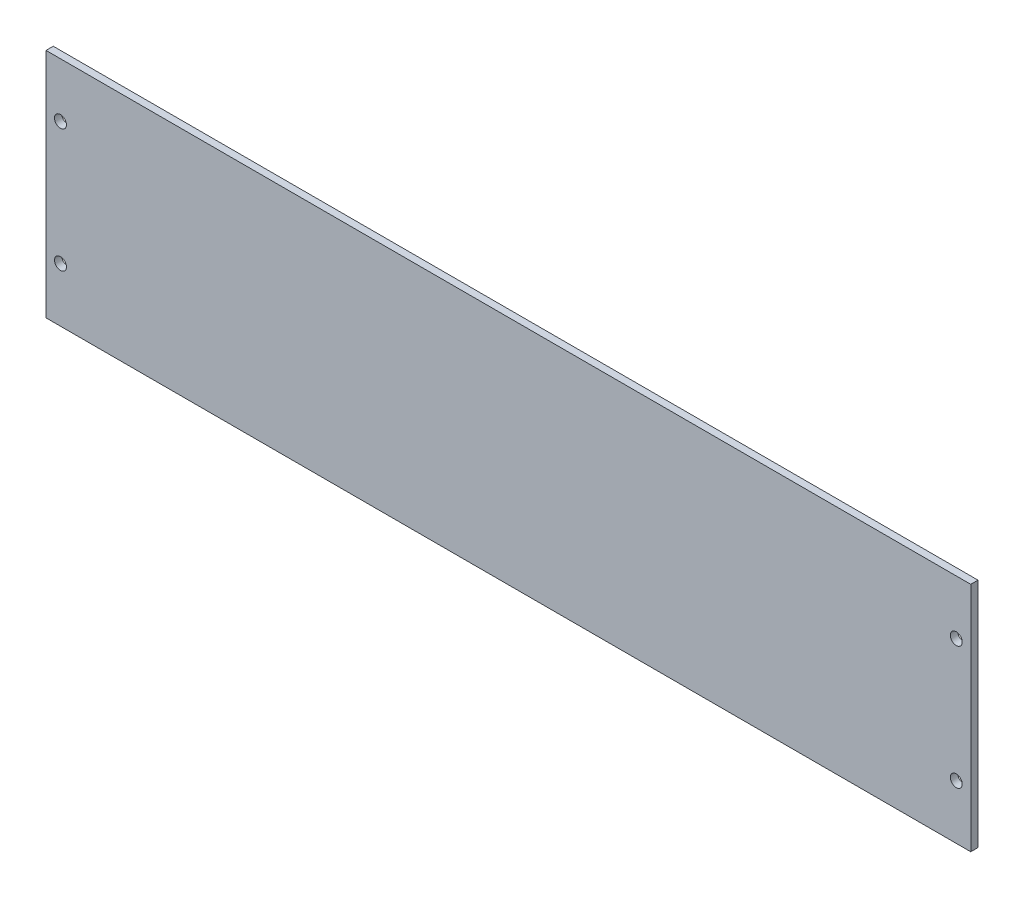
SolidWorks part; units mm, degrees
ref_plane "Plan de face" through (0, 0, 0) normal (0, 0, 1) x (1, 0, 0)
ref_plane "Plan de dessus" through (0, 0, 0) normal (0, 1, 0) x (1, 0, 0)
ref_plane "Plan de droite" through (0, 0, 0) normal (1, 0, 0) x (0, 0, -1)
sketch "Esquisse1" plane through (0, 0, 0) normal (0, 0, 1) x (1, 0, 0)
  line L1 (-255.5, -64) -> (255.5, -64)
  line L2 (-255.5, -64) -> (-255.5, 64)
  line L3 (-255.5, 64) -> (255.5, 64)
  line L4 (255.5, -64) -> (255.5, 64)
  line L5 (-255.5, -64) -> (255.5, 64) construction
  line L6 (-255.5, 64) -> (255.5, -64) construction
  point P0 (0, 0)
  dimension "D1" = 128
  dimension "D2" = 511
extrude "Boss.-Extru.1" add sketch "Esquisse1" along normal blind 4
sketch "Esquisse2" plane through (0, 0, 0) normal (0, 0, -1) x (-1, 0, 0)
  line L0 (255.5, -64) -> (-255.5, -64) construction
  line L1 (247.5, -56) -> (-247.5, -56) construction
  line L2 (247.5, -56) -> (247.5, 56) construction
  line L3 (247.5, 56) -> (-247.5, 56) construction
  line L4 (-247.5, -56) -> (-247.5, 56) construction
  line L5 (247.5, -56) -> (-247.5, 56) construction
  line L6 (247.5, 56) -> (-247.5, -56) construction
  line L7 (-255.5, -64) -> (-255.5, 64) construction
  line L8 (-153.9304, 0) -> (204.6118, 0) construction
  line L9 (0, -141.2759) -> (0, 199.6584) construction
  point P0 (0, 0)
  point P14 (-247.5, -34)
  point P15 (-247.5, 34)
  point P16 (247.5, -34)
  point P17 (247.5, 34)
  point P18 (0, 56)
  dimension "D1" = 8
  dimension "D2" = 8
  dimension "D3" = 30
hole_wizard "Dégagement M61" positions "Esquisse3D1" profile "Esquisse3" hole size "M6" standard "ISO" end condition through all
sketch3d "Esquisse3D1"
  point P3 (-247.5, 34, 0)
  point P6 (-247.5, -34, 0)
  point P9 (247.5, -34, 0)
  point P12 (247.5, 34, 0)
sketch "Esquisse3" plane through (-247.5, 34, 0) normal (1, 0, 0) x (0, 1, 0)
  line L0 (0, 0) -> (0, 4)
  line L1 (0, 4) -> (3.3, 4)
  line L2 (3.3, 4) -> (3.3, 0)
  line L5 (3.3, 0) -> (0, 0)
  line L11 (0, -6.35) -> (0, 107.95) construction
  dimension "Diamètre du perçage jusqu'au prochain" = 6.6
  dimension "Profondeur du perçage jusqu'au prochain" = 4
